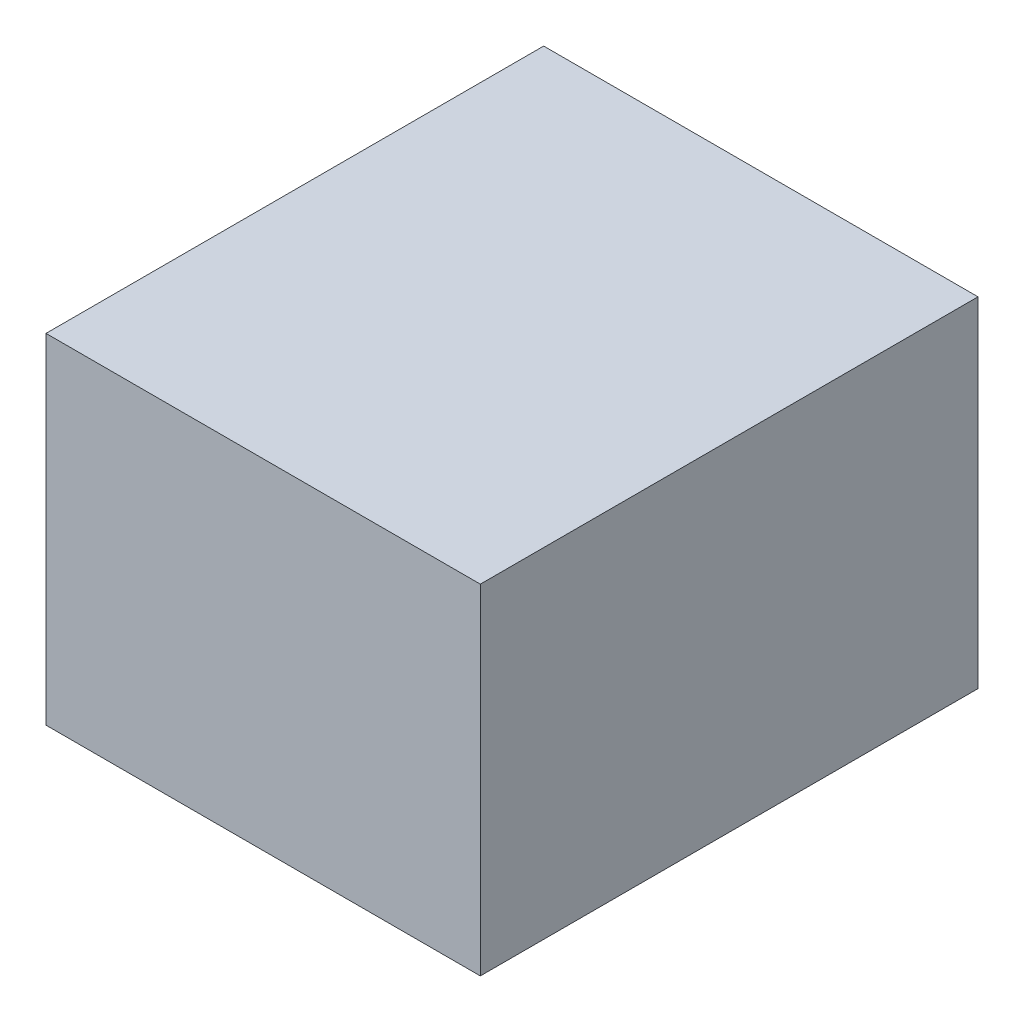
SolidWorks part; units mm, degrees
ref_plane "Front" through (0, 0, 0) normal (0, 0, 1) x (1, 0, 0)
ref_plane "Top" through (0, 0, 0) normal (0, 1, 0) x (1, 0, 0)
ref_plane "Right" through (0, 0, 0) normal (1, 0, 0) x (0, 0, -1)
sketch "Sketch1" plane through (0, 0, 0) normal (0, 1, 0) x (1, 0, 0)
  line L1 (-24, -27.5) -> (24, -27.5)
  line L2 (-24, -27.5) -> (-24, 27.5)
  line L3 (-24, 27.5) -> (24, 27.5)
  line L4 (24, -27.5) -> (24, 27.5)
  line L5 (-24, -27.5) -> (24, 27.5) construction
  line L6 (-24, 27.5) -> (24, -27.5) construction
  point P0 (0, 0)
  dimension "D1" = 55
  dimension "D2" = 48
extrude "Boss-Extrude1" add sketch "Sketch1" along normal blind 37.5
